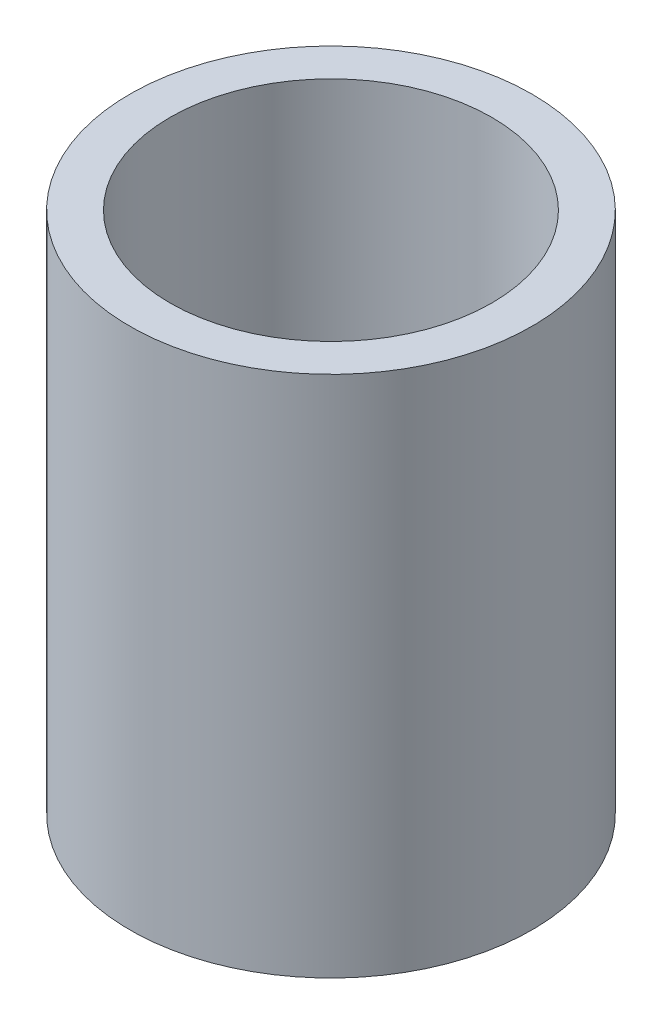
SolidWorks part; units mm, degrees
ref_plane "Front Plane" through (0, 0, 0) normal (0, 0, 1) x (1, 0, 0)
ref_plane "Top Plane" through (0, 0, 0) normal (0, 1, 0) x (1, 0, 0)
ref_plane "Right Plane" through (0, 0, 0) normal (1, 0, 0) x (0, 0, -1)
sketch "Sketch1" plane through (0, 0, 0) normal (0, 1, 0) x (1, 0, 0)
  circle A0 centre (0, 0) radius 4
  circle A1 centre (0, 0) radius 5
  dimension "D1" = 8
  dimension "D2" = 10
extrude "Boss-Extrude1" add sketch "Sketch1" along normal blind 13
